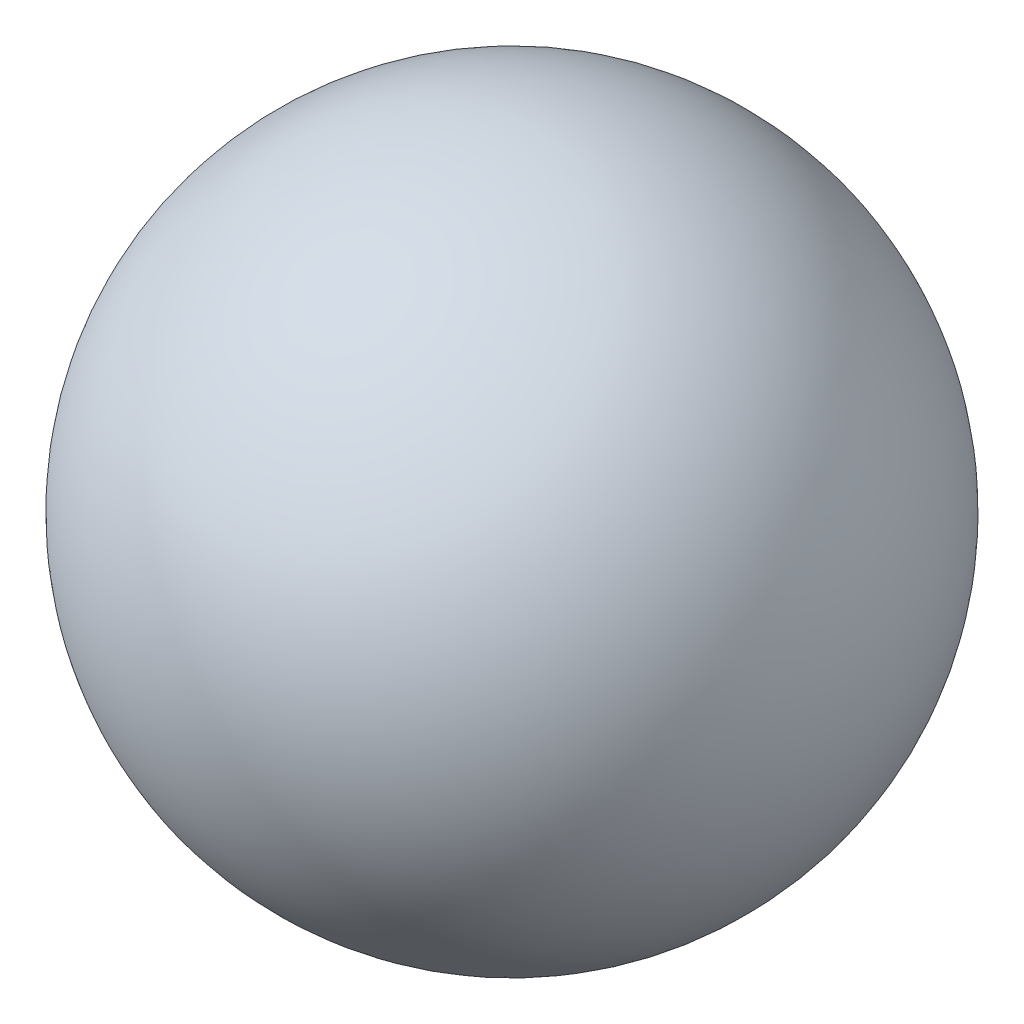
SolidWorks part; units mm, degrees
material "Rubber"
ref_plane "Front Plane" through (0, 0, 0) normal (0, 0, 1) x (1, 0, 0)
ref_plane "Top Plane" through (0, 0, 0) normal (0, 1, 0) x (1, 0, 0)
ref_plane "Right Plane" through (0, 0, 0) normal (1, 0, 0) x (0, 0, -1)
sketch "Sketch1" plane through (0, 0, 0) normal (0, 1, 0) x (1, 0, 0)
  line L0 (0, 0) -> (0, 20.32)
  line L1 (0, 0) -> (0, -20.32)
  arc A0 (0, -20.32) -> (0, 20.32) centre (0, 0) ccw
  dimension "D1" = 20.32
revolve "Revolve1" add sketch "Sketch1" angle 360 about L1
